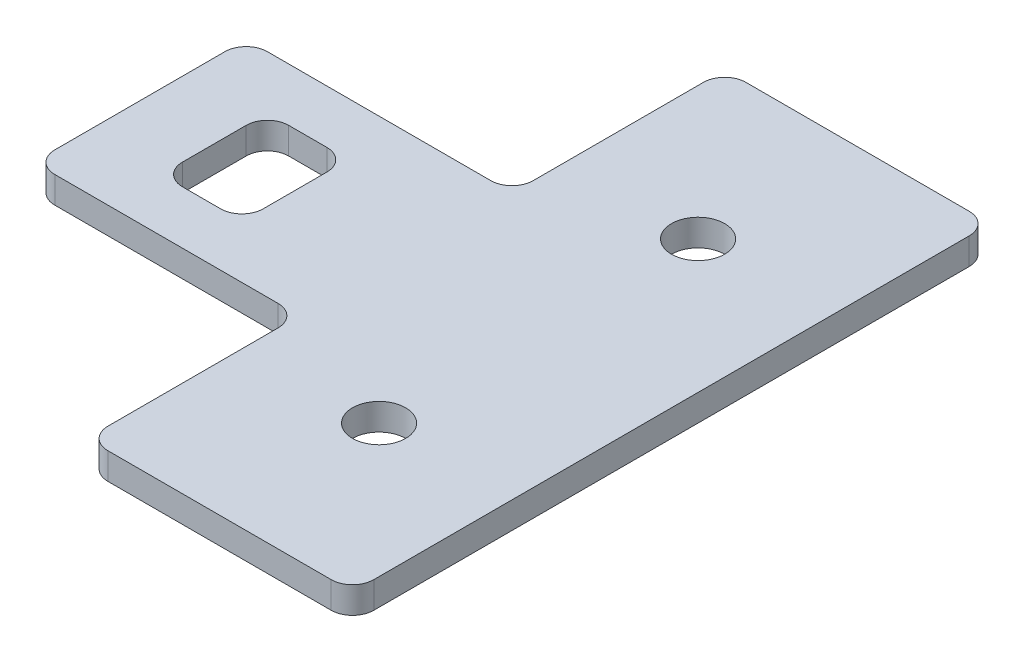
SolidWorks part; units mm, degrees
ref_plane "Front Plane" through (0, 0, 0) normal (0, 0, 1) x (1, 0, 0)
ref_plane "Top Plane" through (0, 0, 0) normal (0, 1, 0) x (1, 0, 0)
ref_plane "Right Plane" through (0, 0, 0) normal (1, 0, 0) x (0, 0, -1)
sketch "Sketch1" plane through (0, 0, 0) normal (0, 1, 0) x (1, 0, 0)
  line L0 (-38.4255, 0) -> (31.75, 0) construction
  line L21 (2.54, -38.1) -> (29.21, -38.1)
  line L22 (-31.75, -10.16) -> (-31.75, 10.16)
  line L23 (2.54, 38.1) -> (29.21, 38.1)
  line L28 (31.75, -35.56) -> (31.75, 35.56)
  line L30 (-29.21, 12.7) -> (-2.54, 12.7)
  line L39 (31.75, 0) -> (0, 38.1) construction
  line L40 (0, 38.1) -> (0, -38.1) construction
  line L41 (0, -38.1) -> (31.75, 0) construction
  line L51 (-29.21, -12.7) -> (-2.54, -12.7)
  line L52 (0, 15.24) -> (0, 35.56)
  line L53 (0, -15.24) -> (0, -35.56)
  line L57 (-20.32, -6.35) -> (-15.748, -6.35)
  line L58 (-22.86, -3.81) -> (-22.86, 3.81)
  line L59 (-20.32, 6.35) -> (-15.748, 6.35)
  line L60 (-13.208, -3.81) -> (-13.208, 3.81)
  circle A10 centre (15.875, 19.05) radius 3.175
  circle A11 centre (15.875, -19.05) radius 3.175
  arc A12 (-20.32, -6.35) -> (-22.86, -3.81) centre (-20.32, -3.81) cw
  arc A13 (-15.748, -6.35) -> (-13.208, -3.81) centre (-15.748, -3.81) ccw
  arc A14 (-15.748, 6.35) -> (-13.208, 3.81) centre (-15.748, 3.81) cw
  arc A15 (-22.86, 3.81) -> (-20.32, 6.35) centre (-20.32, 3.81) cw
  arc A16 (-29.21, -12.7) -> (-31.75, -10.16) centre (-29.21, -10.16) cw
  arc A17 (-2.54, -12.7) -> (0, -15.24) centre (-2.54, -15.24) cw
  arc A18 (0, -35.56) -> (2.54, -38.1) centre (2.54, -35.56) ccw
  arc A19 (29.21, -38.1) -> (31.75, -35.56) centre (29.21, -35.56) ccw
  arc A20 (29.21, 38.1) -> (31.75, 35.56) centre (29.21, 35.56) cw
  arc A21 (0, 35.56) -> (2.54, 38.1) centre (2.54, 35.56) cw
  arc A22 (-2.54, 12.7) -> (0, 15.24) centre (-2.54, 15.24) ccw
  arc A23 (-29.21, 12.7) -> (-31.75, 10.16) centre (-29.21, 10.16) ccw
  point P0 (0, 0)
  point P15 (-18.034, 6.35)
  point P20 (-13.208, -6.35)
  point P23 (-13.208, 6.35)
  point P26 (-22.86, 6.35)
  point P29 (-31.75, -12.7)
  point P36 (0, -12.7)
  point P42 (31.75, -38.1)
  point P45 (31.75, 38.1)
  point P52 (0, 12.7)
  point P55 (-31.75, 12.7)
  dimension "D2" = 15.875
  dimension "D3" = 6.35
  dimension "D4" = 19.05
  dimension "D5" = 31.75
  dimension "D8" = 13.208
  dimension "D12" = 9.652
  dimension "D14" = 2.54
  dimension "D15" = 2.54
  dimension "D6" = 31.75
  dimension "D7" = 12.7
  dimension "D9" = 12.7
  dimension "D10" = 76.2
  dimension "D11" = 6.35
  dimension "D13" = 12.7
extrude "Boss-Extrude1" add sketch "Sketch1" along normal blind 3.175
